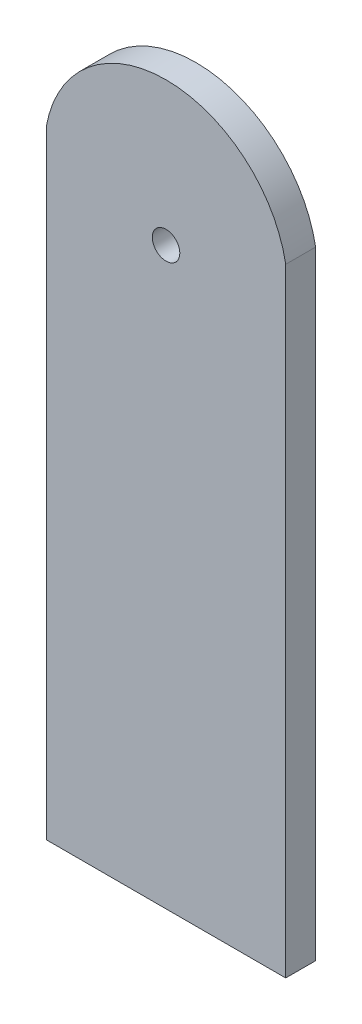
SolidWorks part; units mm, degrees
ref_plane "Front Plane" through (0, 0, 0) normal (0, 0, 1) x (1, 0, 0)
ref_plane "Top Plane" through (0, 0, 0) normal (0, 1, 0) x (1, 0, 0)
ref_plane "Right Plane" through (0, 0, 0) normal (1, 0, 0) x (0, 0, -1)
sketch "Sketch2" plane through (0, 0, 0) normal (0, 0, 1) x (1, 0, 0)
  line L0 (12.7, 76.2) -> (12.7, 0) construction
  line L1 (0, 0) -> (25.4, 0)
  line L2 (0, 0) -> (0, 65.5927)
  line L4 (25.4, 0) -> (25.4, 65.5927)
  circle A0 centre (12.7, 60.9944) radius 1.4605
  arc A1 (0, 65.5927) -> (25.4, 65.5927) centre (12.7, 63.2936) cw
  dimension "D3" = 2.921
  dimension "D2" = 25.4
extrude "Boss-Extrude1" add sketch "Sketch2" along normal blind 3.175
